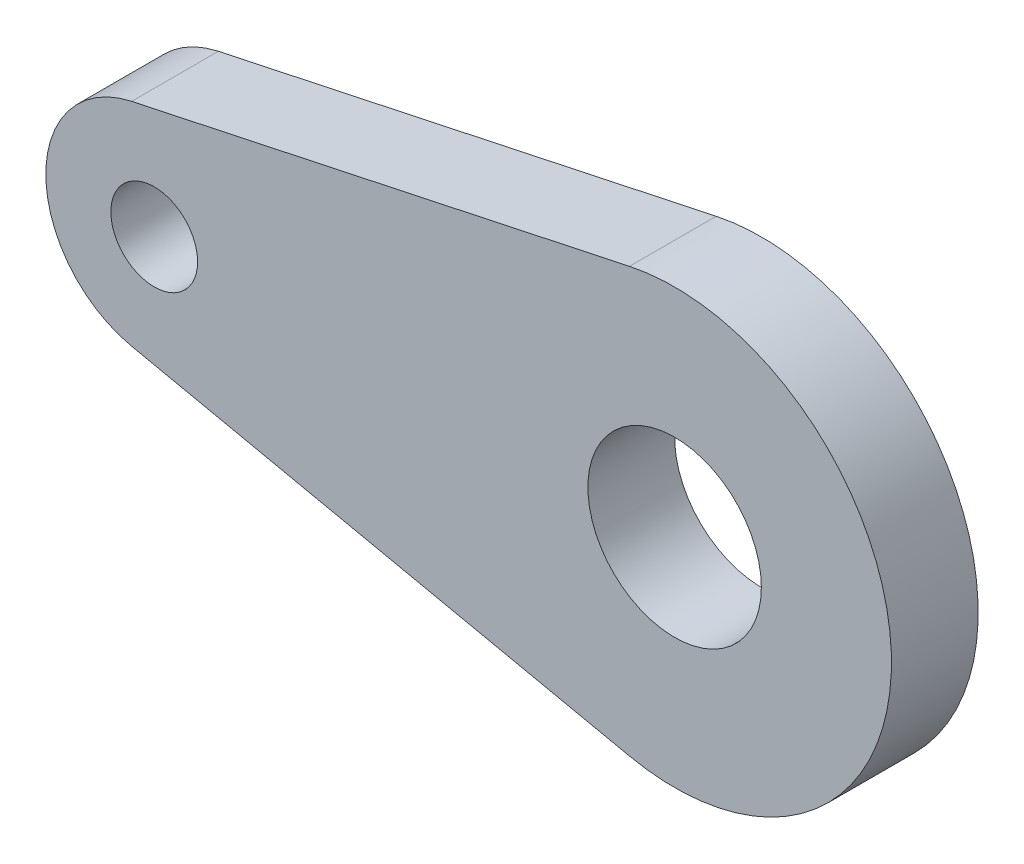
SolidWorks part; units mm, degrees
ref_plane "Front Plane" through (0, 0, 0) normal (0, 0, 1) x (1, 0, 0)
ref_plane "Top Plane" through (0, 0, 0) normal (0, 1, 0) x (1, 0, 0)
ref_plane "Right Plane" through (0, 0, 0) normal (1, 0, 0) x (0, 0, -1)
sketch "Sketch1" plane through (0, 0, 0) normal (0, 0, 1) x (1, 0, 0)
  line L0 (0, 0) -> (-76.2, 0) construction
  line L1 (55, 0) -> (-55, 0) construction
  line L2 (-79.5073, -15.5267) -> (-6.6146, -31.0533)
  line L3 (-79.5073, 15.5267) -> (-6.6146, 31.0533)
  circle A0 centre (-76.2, 0) radius 6.35
  circle A1 centre (0, 0) radius 12.7
  arc A2 (-79.5073, 15.5267) -> (-79.5073, -15.5267) centre (-76.2, 0) ccw
  arc A3 (-6.6146, -31.0533) -> (-6.6146, 31.0533) centre (0, 0) ccw
  point P13 (0, 0)
  dimension "D2" = 25.4
  dimension "D3" = 12.7
  dimension "D1" = 76.2
extrude "Boss-Extrude1" add sketch "Sketch1" along normal blind 12.7
